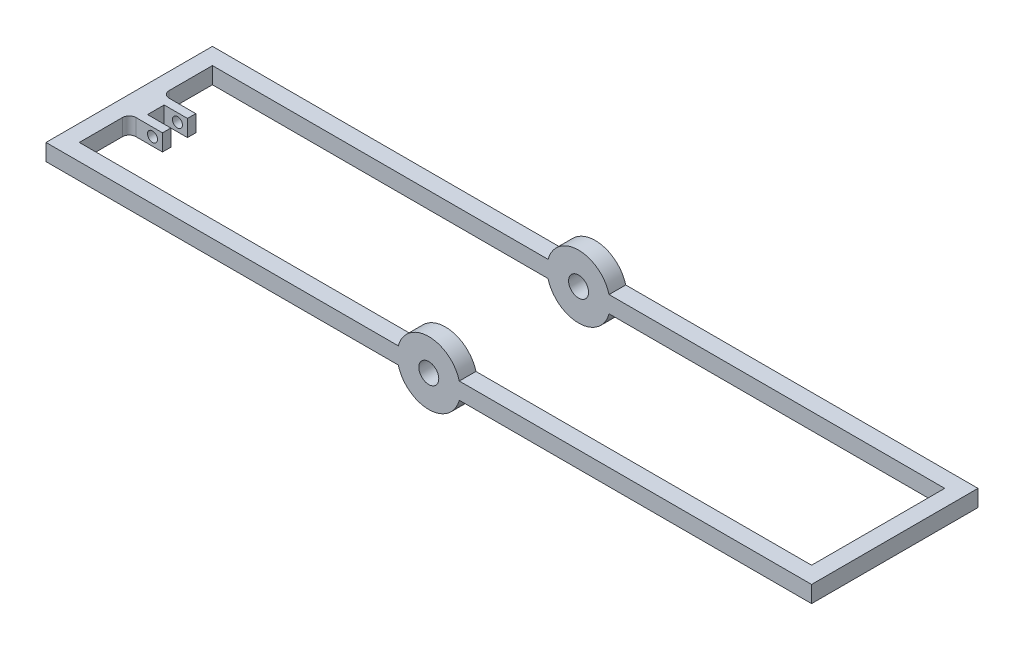
SolidWorks part; units mm, degrees
ref_plane "Front Plane" through (0, 0, 0) normal (0, 0, 1) x (1, 0, 0)
ref_plane "Top Plane" through (0, 0, 0) normal (0, 1, 0) x (1, 0, 0)
ref_plane "Right Plane" through (0, 0, 0) normal (1, 0, 0) x (0, 0, -1)
sketch "Sketch1" plane through (0, 0, 0) normal (0, 0, 1) x (1, 0, 0)
  line L0 (124.1652, 0) -> (230, 0)
  line L1 (0, 0) -> (105.8348, 0)
  line L2 (0, 0) -> (0, 5)
  line L3 (0, 5) -> (105.8348, 5)
  line L4 (230, 0) -> (230, 5)
  line L5 (124.1652, 5) -> (230, 5)
  arc A0 (124.1652, 5) -> (105.8348, 5) centre (115, 2.5) ccw
  circle A1 centre (115, 2.5) radius 3
  arc A2 (105.8348, 0) -> (124.1652, 0) centre (115, 2.5) ccw
  dimension "D4" = 19
  dimension "D5" = 6
  dimension "D1" = 230
  dimension "D2" = 5
  dimension "D3" = 115
  dimension "D6" = 2.5
extrude "Boss-Extrude1" add sketch "Sketch1" along normal blind 50
sketch "Sketch2" plane through (0, 0, 0) normal (0, -1, 0) x (-1, 0, 0)
  line L0 (0, -50) -> (-105.8348, -50) construction
  line L1 (-5, -45) -> (-225, -45)
  line L2 (-5, -45) -> (-5, -5)
  line L3 (-5, -5) -> (-225, -5)
  line L4 (-225, -45) -> (-225, -5)
  line L5 (-5, -45) -> (-225, -5) construction
  line L6 (-5, -5) -> (-225, -45) construction
  line L7 (0, 0) -> (-105.8348, 0) construction
  line L8 (0, -50) -> (0, 0) construction
  line L9 (-230, -50) -> (-230, 0) construction
  point P0 (-115, -25)
  dimension "D1" = 5
  dimension "D2" = 5
  dimension "D3" = 5
  dimension "D4" = 5
extrude "Cut-Extrude1" cut sketch "Sketch2" against normal through all both and the other way through all
sketch "Sketch3" plane through (5, 0, 0) normal (1, 0, 0) x (0, 0, -1)
  line L0 (-5, 0) -> (-45, 0) construction
  line L1 (-20, 5) -> (-30, 5)
  line L2 (-20, 5) -> (-20, 0)
  line L3 (-20, 0) -> (-30, 0)
  line L4 (-30, 5) -> (-30, 0)
  line L5 (-20, 5) -> (-30, 0) construction
  line L6 (-20, 0) -> (-30, 5) construction
  line L7 (-45, 5) -> (-45, 0) construction
  point P0 (-25, 2.5)
  dimension "D1" = 10
  dimension "D2" = 5
  dimension "D3" = 20
extrude "Boss-Extrude2" add sketch "Sketch3" along normal blind 10
sketch "Sketch4" plane through (0, 5, 0) normal (0, 1, 0) x (1, 0, 0)
  line L0 (15, -20) -> (15, -30) construction
  line L1 (8, -27.5) -> (15, -27.5)
  line L2 (8, -27.5) -> (8, -22.5)
  line L3 (8, -22.5) -> (15, -22.5)
  line L4 (15, -27.5) -> (15, -22.5)
  line L5 (8, -27.5) -> (15, -22.5) construction
  line L6 (8, -22.5) -> (15, -27.5) construction
  line L7 (15, -30) -> (5, -30) construction
  point P0 (11.5, -25)
  dimension "D1" = 7
  dimension "D2" = 5
  dimension "D3" = 5
extrude "Cut-Extrude2" cut sketch "Sketch4" against normal up to next
fillet "Fillet1" radius 2 2 edges at (5, 2.5, 30) (5, 2.5, 20)
sketch "Sketch5" plane through (0, 0, 20) normal (0, 0, -1) x (-1, 0, 0)
  line L0 (-15, 0) -> (-15, 5) construction
  circle A0 centre (-12, 2.5) radius 1.5
  dimension "D1" = 3
extrude "Cut-Extrude3" cut sketch "Sketch5" against normal blind 10
